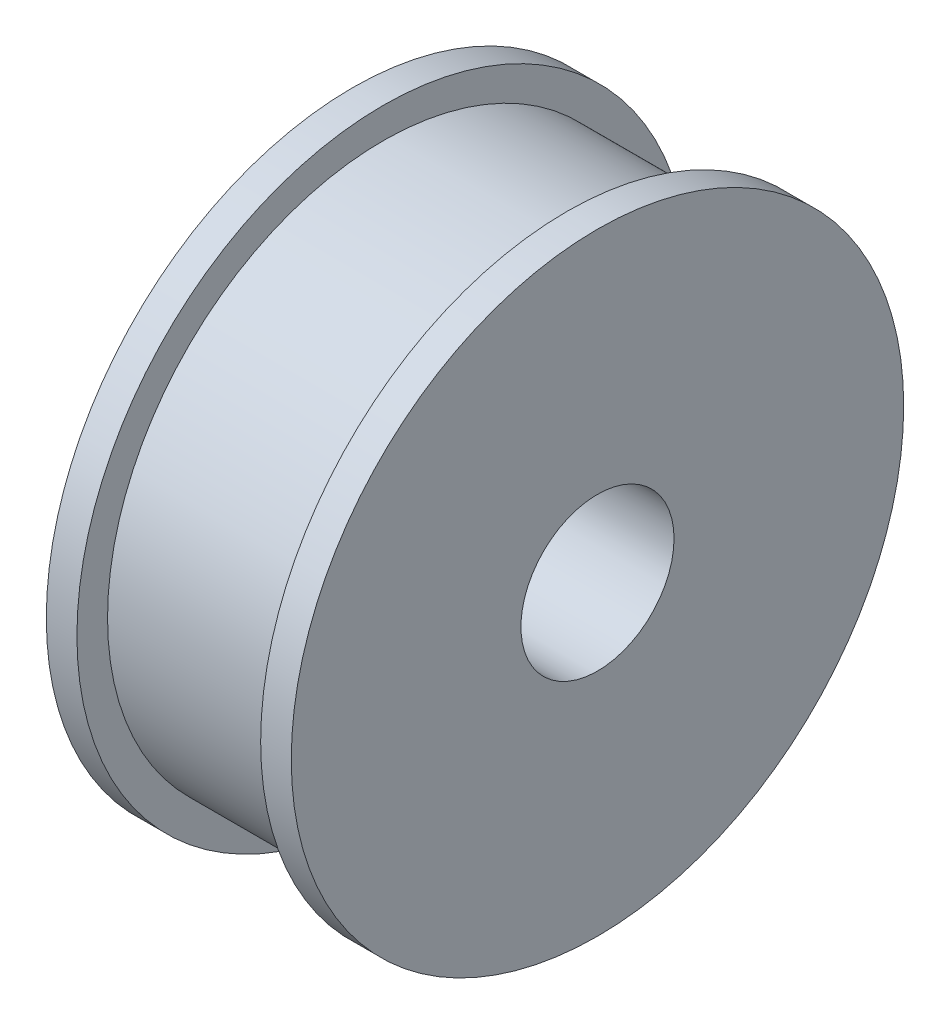
SolidWorks part; units mm, degrees
ref_plane "Front Plane" through (0, 0, 0) normal (0, 0, 1) x (1, 0, 0)
ref_plane "Top Plane" through (0, 0, 0) normal (0, 1, 0) x (1, 0, 0)
ref_plane "Right Plane" through (0, 0, 0) normal (1, 0, 0) x (0, 0, -1)
sketch "Sketch2" plane through (0, 0, 0) normal (0, 0, 1) x (1, 0, 0)
  line L0 (-12.2716, 0) -> (15.0514, 0) construction
  line L1 (5.08, 0) -> (-5.08, 0)
  line L2 (-5.08, 0) -> (-5.08, 12.7)
  line L5 (5.08, 12.7) -> (5.08, 0)
  line L6 (-5.08, 12.7) -> (-3.81, 12.7)
  line L7 (-3.81, 12.7) -> (-3.81, 11.43)
  line L8 (-3.81, 11.43) -> (3.81, 11.43)
  line L9 (3.81, 11.43) -> (3.81, 12.7)
  line L10 (3.81, 12.7) -> (5.08, 12.7)
  dimension "D1" = 12.7
  dimension "D2" = 10.16
  dimension "D3" = 7.62
  dimension "D4" = 1.27
revolve "Revolve1" add sketch "Sketch2" angle 360 about L0
sketch "Sketch3" plane through (5.08, 0, 0) normal (1, 0, 0) x (0, 0, -1)
  circle A0 centre (0, 0) radius 3.175
  dimension "D1" = 6.35
extrude "Cut-Extrude1" cut sketch "Sketch3" against normal up to next
